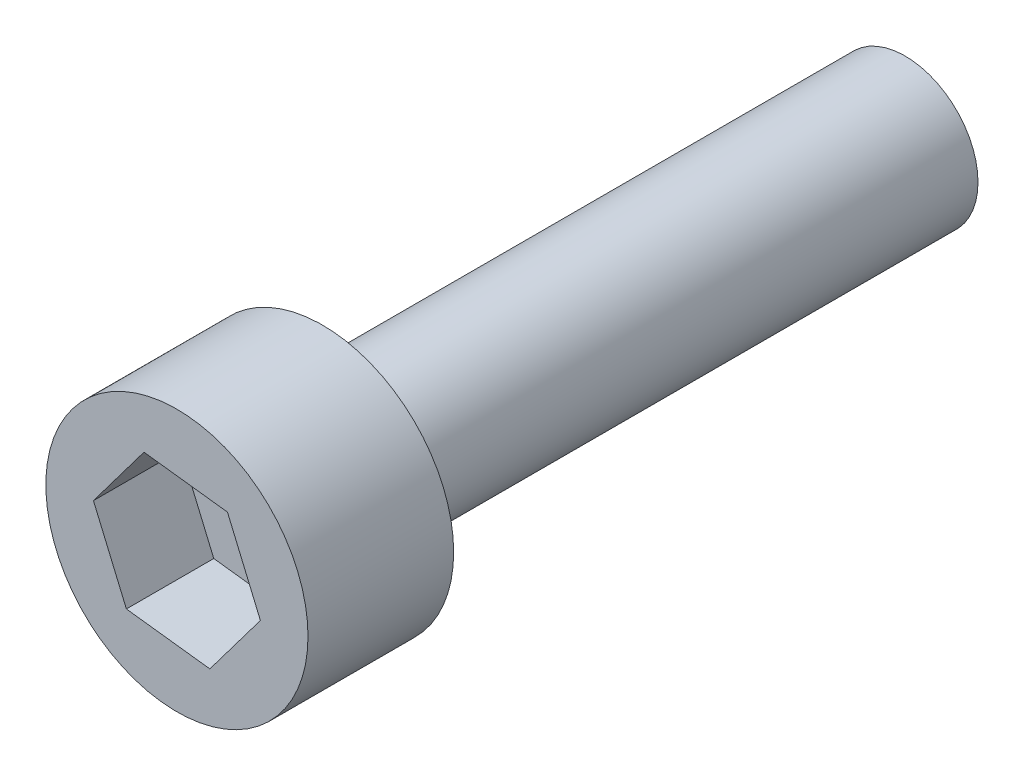
SolidWorks part; units mm, degrees
ref_plane "Plan de face" through (0, 0, 0) normal (0, 0, 1) x (1, 0, 0)
ref_plane "Plan de dessus" through (0, 0, 0) normal (0, 1, 0) x (1, 0, 0)
ref_plane "Plan de droite" through (0, 0, 0) normal (1, 0, 0) x (0, 0, -1)
sketch "Esquisse1" plane through (0, 0, 0) normal (0, 0, 1) x (1, 0, 0)
  circle A0 centre (0, 0) radius 1.25
  dimension "D1" = 2.5
extrude "Boss.-Extru.1" add sketch "Esquisse1" along normal blind 10
sketch "Esquisse2" plane through (0, 0, 10) normal (0, 0, 1) x (1, 0, 0)
  circle A0 centre (0, 0) radius 2.25
  dimension "D1" = 4.5
extrude "Boss.-Extru.2" add sketch "Esquisse2" along normal blind 2.5
sketch "Esquisse3" plane through (0, 0, 12.5) normal (0, 0, 1) x (1, 0, 0)
  line L1 (1.4328, -0.1744) -> (0.8675, 1.1536)
  line L2 (0.8675, 1.1536) -> (-0.5653, 1.3281)
  line L3 (-0.5653, 1.3281) -> (-1.4328, 0.1744)
  line L4 (-1.4328, 0.1744) -> (-0.8675, -1.1536)
  line L5 (-0.8675, -1.1536) -> (0.5653, -1.3281)
  line L6 (0.5653, -1.3281) -> (1.4328, -0.1744)
  circle A0 centre (0, 0) radius 1.25 construction
  dimension "D1" = 2.5
extrude "Enlèv. mat.-Extru.1" cut sketch "Esquisse3" against normal blind 1.5
